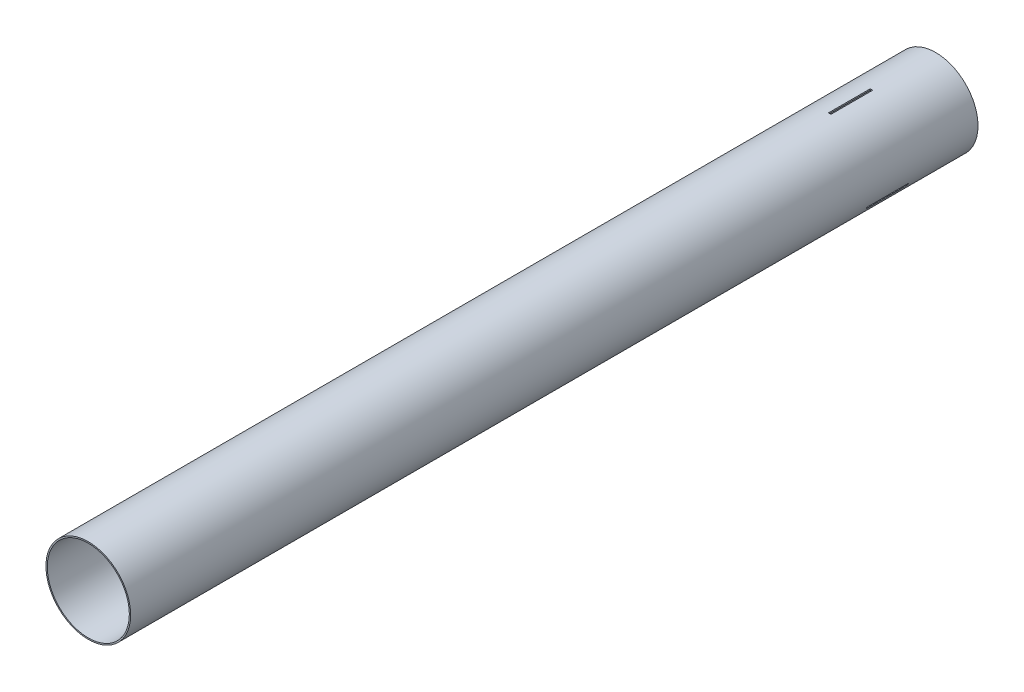
SolidWorks part; units mm, degrees
material "E-Glass Fiber"
ref_plane "Front Plane" through (0, 0, 0) normal (0, 0, 1) x (1, 0, 0)
ref_plane "Top Plane" through (0, 0, 0) normal (0, 1, 0) x (1, 0, 0)
ref_plane "Right Plane" through (0, 0, 0) normal (1, 0, 0) x (0, 0, -1)
sketch "Sketch1" plane through (0, 0, 0) normal (0, 0, 1) x (1, 0, 0)
  circle A0 centre (0, 0) radius 49.2125
  circle A1 centre (0, 0) radius 50.8
  dimension "D1" = 1.5875
  dimension "D2" = 101.6
extrude "Boss-Extrude1" add sketch "Sketch1" along normal blind 1016
sketch "Sketch2" plane through (0, 0, 0) normal (0, 0, 1) x (1, 0, 0)
  line L0 (25.0202, -16.1759) -> (26.5188, -13.5802)
  line L1 (1.4986, 30.1625) -> (-1.4986, 30.1625)
  line L2 (1.4986, 30.1625) -> (1.4986, 68.2625)
  line L3 (1.4986, 68.2625) -> (-1.4986, 68.2625)
  line L4 (-1.4986, 30.1625) -> (-1.4986, 68.2625)
  line L5 (1.4986, 30.1625) -> (-1.4986, 68.2625) construction
  line L6 (1.4986, 68.2625) -> (-1.4986, 30.1625) construction
  line L7 (25.0202, -16.1759) -> (58.0158, -35.2259)
  line L8 (58.0158, -35.2259) -> (59.5144, -32.6302)
  line L9 (26.5188, -13.5802) -> (59.5144, -32.6302)
  line L10 (25.0202, -16.1759) -> (59.5144, -32.6302) construction
  line L11 (58.0158, -35.2259) -> (26.5188, -13.5802) construction
  line L12 (-26.8708, -13.377) -> (-25.3722, -15.9727)
  line L13 (-26.8708, -13.377) -> (-59.8664, -32.427)
  line L14 (-59.8664, -32.427) -> (-58.3678, -35.0227)
  line L15 (-25.3722, -15.9727) -> (-58.3678, -35.0227)
  line L16 (-26.8708, -13.377) -> (-58.3678, -35.0227) construction
  line L17 (-59.8664, -32.427) -> (-25.3722, -15.9727) construction
  circle A0 centre (0, 0) radius 49.2125 construction
  point P0 (0, 49.2125)
  point P7 (0, 30.1625)
  point P11 (42.2673, -24.403)
  point P16 (-42.6193, -24.1999)
  point P21 (-0.1173, 0.2032)
  dimension "D1" = 38.1
  dimension "D2" = 2.9972
  dimension "D3" = 3
extrude "Cut-Extrude1" cut sketch "Sketch2" against normal blind 50.0126 from offset 127
sketch "Sketch3" plane through (0, 0, 0) normal (0, 1, 0) x (1, 0, 0)
  line L0 (0, 0) -> (0, -1016) construction
  line L1 (-50.8, -1016) -> (50.8, -1016) construction
